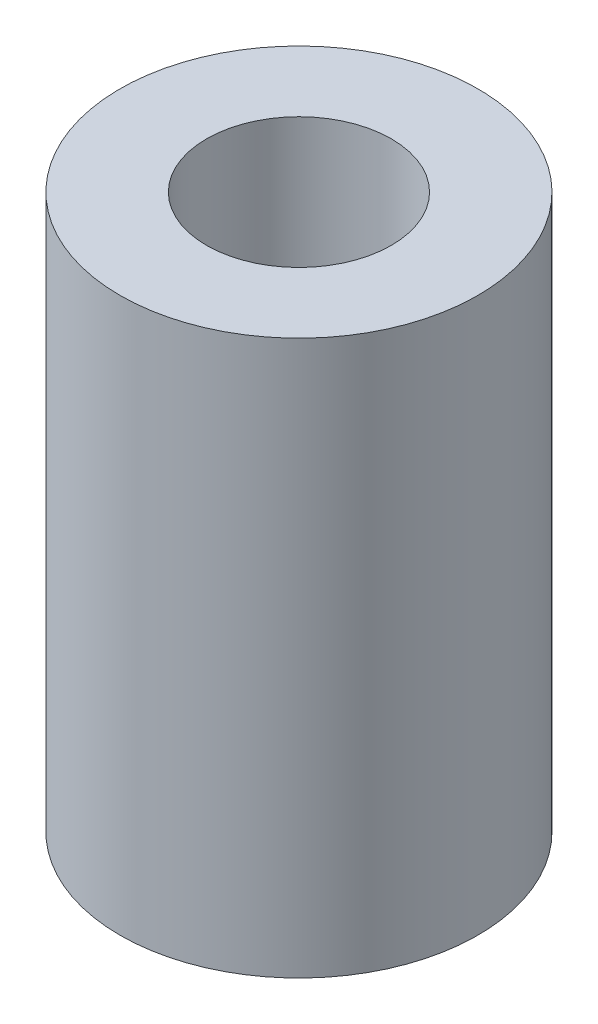
SolidWorks part; units mm, degrees
ref_plane "Front Plane" through (0, 0, 0) normal (0, 0, 1) x (1, 0, 0)
ref_plane "Top Plane" through (0, 0, 0) normal (0, 1, 0) x (1, 0, 0)
ref_plane "Right Plane" through (0, 0, 0) normal (1, 0, 0) x (0, 0, -1)
sketch "Sketch1" plane through (0, 0, 0) normal (0, 1, 0) x (1, 0, 0)
  circle A0 centre (0, 0) radius 4
  circle A1 centre (0, 0) radius 7.75
  dimension "D1" = 8
  dimension "D2" = 15.5
extrude "Boss-Extrude1" add sketch "Sketch1" along normal blind 24
